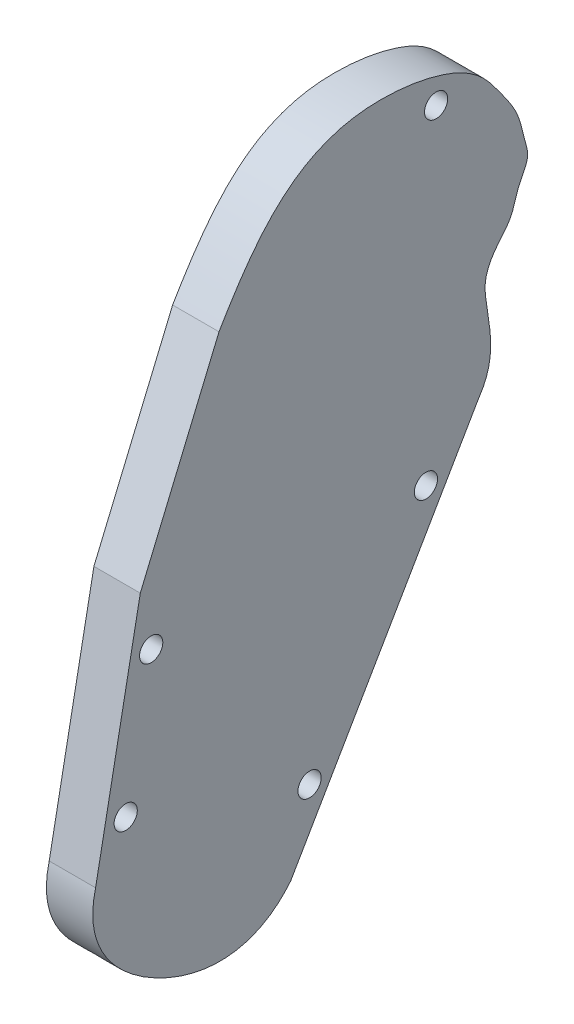
SolidWorks part; units mm, degrees
ref_plane "Front Plane" through (0, 0, 0) normal (0, 0, 1) x (1, 0, 0)
ref_plane "Top Plane" through (0, 0, 0) normal (0, 1, 0) x (1, 0, 0)
ref_plane "Right Plane" through (0, 0, 0) normal (1, 0, 0) x (0, 0, -1)
sketch "Sketch1" plane through (0, 0, 0) normal (1, 0, 0) x (0, 0, -1)
  line L0 (-22.743, -21.8561) -> (-17.9229, 3.2427)
  line L1 (-17.9229, 3.2427) -> (-9.439, 23.3959)
  line L2 (18.5765, 3.2427) -> (-1.7156, -31.7391)
  spline S0 degree 3 poles (-22.743, -21.8561) (-24.1424, -27.3028) (-16.6039, -35.6647) (-5.5981, -36.5145) (-1.7156, -31.7391) knots 0 0 0 0 0.48419 1 1 1 1
  spline S1 degree 3 poles (18.5765, 3.2427) (20.3999, 5.8715) (19.6867, 9.3922) (19.0567, 13.8193) (20.2071, 16.2847) (22.2362, 18.1541) (22.6647, 20.9001) (24.1424, 22.8746) (23.3712, 25.1104) (22.9232, 27.7566) (21.0205, 30.3604) (19.1115, 33.0147) (16.8206, 34.5538) (13.5726, 35.7835) (9.2414, 36.5145) (4.1127, 36.2299) (-3.4789, 33.0863) (-7.1174, 27.3181) (-9.439, 23.3959) knots 0 0 0 0 0.124664 0.161438 0.19566 0.241957 0.280315 0.317452 0.342381 0.380427 0.438288 0.482854 0.526779 0.559206 0.638222 0.721837 0.785952 1 1 1 1
extrude "Boss-Extrude1" add sketch "Sketch1" against normal blind 5
sketch "Sketch2" plane through (53, 0, 0) normal (1, 0, 0) x (0, 0, -1)
  circle A0 centre (-16.7505, -2.583) radius 1.25
  circle A1 centre (-19.496, -16.8792) radius 1.25
  circle A2 centre (0.3228, -23.7409) radius 1.25
  circle A3 centre (12.867, -2.1159) radius 1.25
  circle A4 centre (13.9632, 32.8296) radius 1.25
  point P15 (0, 0)
  point P16 (0, 0)
  point P17 (0, 0)
  point P18 (0, 0)
  point P19 (0, 0)
  point P20 (0, 0)
extrude "Cut-Extrude2" cut sketch "Sketch2" against normal blind 100
